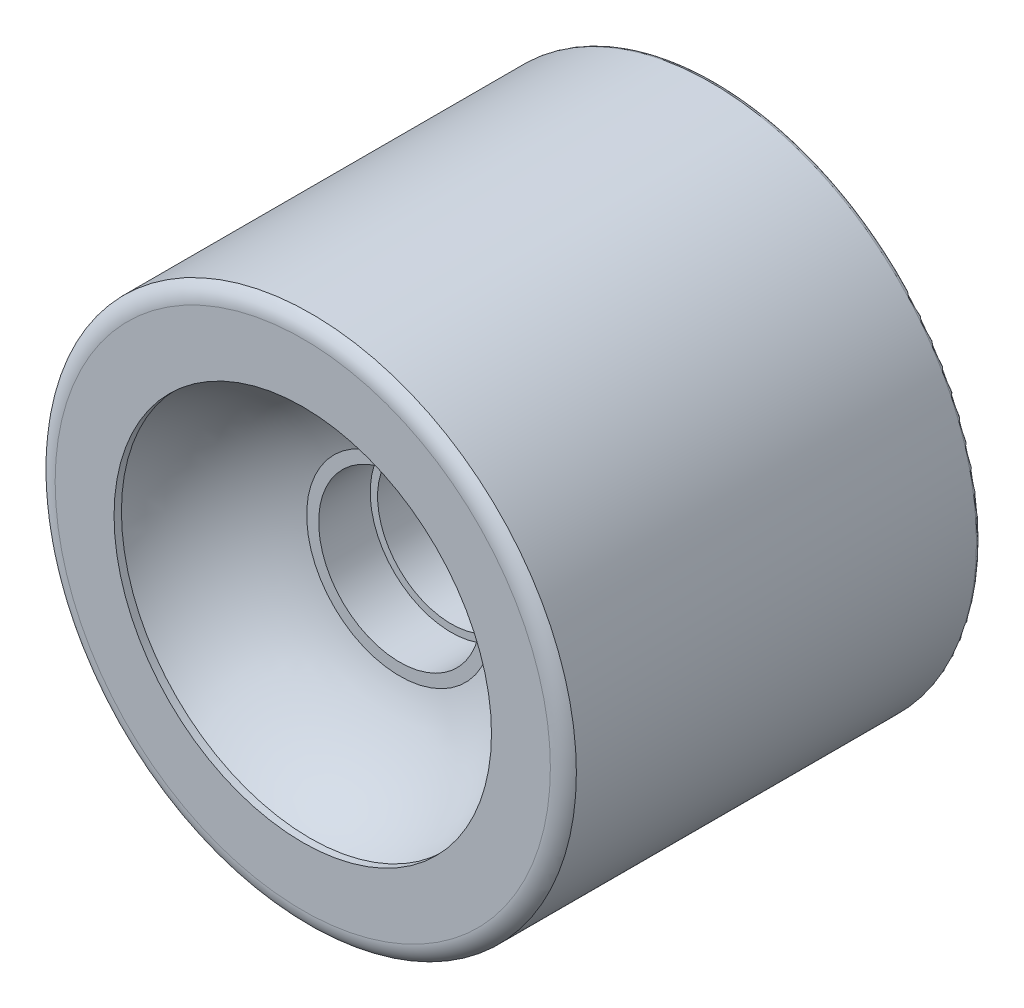
SolidWorks part; units mm, degrees
ref_plane "Front Plane" through (0, 0, 0) normal (0, 0, 1) x (1, 0, 0)
ref_plane "Top Plane" through (0, 0, 0) normal (0, 1, 0) x (1, 0, 0)
ref_plane "Right Plane" through (0, 0, 0) normal (1, 0, 0) x (0, 0, -1)
sketch "Sketch1" plane through (0, 0, 0) normal (0, 1, 0) x (1, 0, 0)
  line L0 (0, 0) -> (0, 44.9507) construction
  line L1 (36, 56) -> (36, 1.1607)
  line L2 (33.63, 0) -> (25.63, 0)
  line L3 (25.63, 0) -> (25.63, 1)
  line L4 (11, 13.16) -> (11, 20.16)
  line L5 (11, 20.16) -> (10, 20.16)
  line L6 (10, 20.16) -> (10, 30.16)
  line L7 (10, 30.16) -> (11, 30.16)
  line L8 (11, 30.16) -> (11, 37.16)
  line L9 (11, 37.16) -> (12.63, 37.16)
  line L10 (13.9115, 40.0942) -> (30, 55)
  line L11 (30, 55) -> (30, 56)
  line L12 (30, 56) -> (36, 56)
  line L13 (11, 13.16) -> (12.63, 13.16)
  arc A0 (36, 1.1607) -> (33.63, 0) centre (33.63, 3) cw
  arc A1 (25.63, 1) -> (12.63, 13.16) centre (6.8951, -6.0001) ccw
  arc A2 (12.63, 37.16) -> (13.9115, 40.0942) centre (16.63, 37.16) cw
  dimension "D8" = 20
  dimension "D13" = 3
  dimension "D16" = 4
  dimension "D1" = 56
  dimension "D2" = 72
  dimension "D3" = 22
  dimension "D4" = 10
  dimension "D5" = 13.16
  dimension "D6" = 1
  dimension "D7" = 1.63
  dimension "D9" = 1
  dimension "D10" = 7
  dimension "D11" = 8
  dimension "D12" = 13
  dimension "D14" = 6
  dimension "D15" = 1
revolve "Revolve1" add sketch "Sketch1" angle 360 about L0
fillet "Fillet1" radius 0.5 1 edges at (36, 0, -56)
